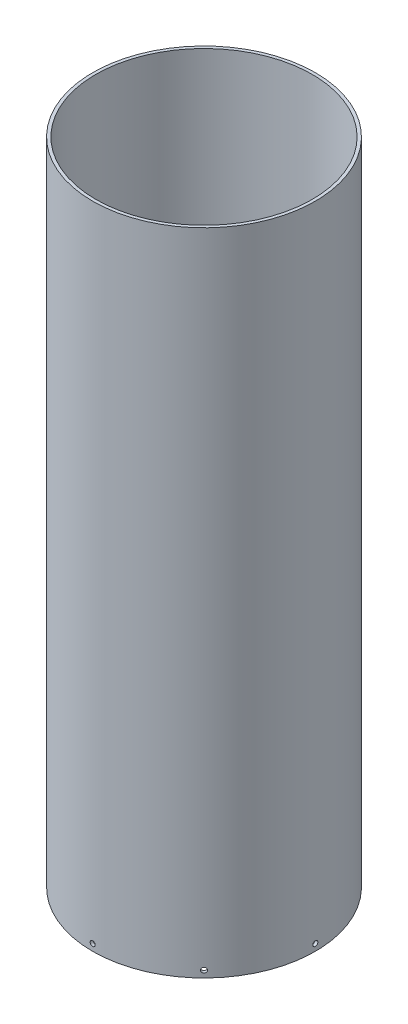
SolidWorks part; units mm, degrees
ref_plane "Front Plane" through (0, 0, 0) normal (0, 0, 1) x (1, 0, 0)
ref_plane "Top Plane" through (0, 0, 0) normal (0, 1, 0) x (1, 0, 0)
ref_plane "Right Plane" through (0, 0, 0) normal (1, 0, 0) x (0, 0, -1)
sketch "Sketch1" plane through (0, 0, 0) normal (0, 1, 0) x (1, 0, 0)
  circle A0 centre (0, 0) radius 76.2
  circle A1 centre (0, 0) radius 78.359
  dimension "D1" = 152.4
  dimension "D2" = 156.718
extrude "Boss-Extrude1" add sketch "Sketch1" along normal blind 457.2
ref_axis "Axis1" through (0, 457.2, 0) along (0, -1, 0)
sketch "Sketch2" plane through (0, 0, 0) normal (0, 0, 1) x (1, 0, 0)
  line L0 (0, 0) -> (0, 4.7625) construction
  circle A0 centre (0, 4.7625) radius 1.75
  dimension "D1" = 3.5
  dimension "D2" = 4.7625
extrude "Cut-Extrude1" cut sketch "Sketch2" against normal through all
pattern_circular "CirPattern1" count 8 over 360 about axis through (0, 457.2, 0) along (0, -1, 0) of "Cut-Extrude1"
equation "\"D1@Boss-Extrude1\"=\"Aft_Upper_Length\""
equation "\"AB_Coupling_Section_Length\"= 0.375in"
equation "\"AB_Coupler_Num_Screws\"= 8"
equation "\"AB_Coupling_Screw_Diameter\"= 3.5mm"
equation "\"AB_Coupler_OD_Length\"= 2in"
equation "\"AB_Coupler_Length\"= \"AB_Coupler_OD_Length\" + \"AB_Coupling_Section_Length\" * 2"
equation "\"D1@Sketch2\"=\"AB_Coupling_Screw_Diameter\""
equation "\"D2@Sketch2\"=\"AB_Coupling_Section_Length\"/2"
equation "\"D1@CirPattern1\"=\"AB_Coupler_Num_Screws\""
equation "\"Aft_Section_Length\"= 40in"
equation "\"Aft_Upper_Length\"= \"Aft_Section_Length\" - \"Aft_Lower_Length\" - \"AB_Coupler_OD_Length\""
equation "\"Aft_Lower_Length\"= 20in"
